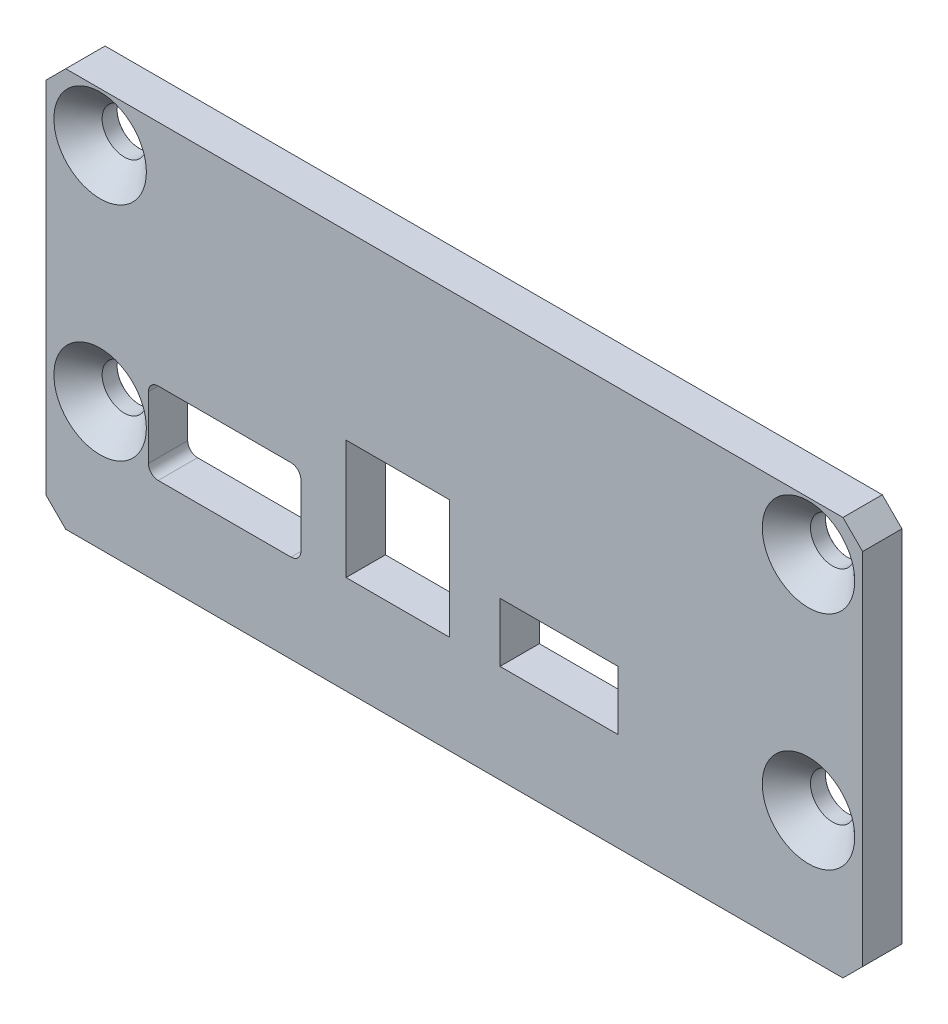
SolidWorks part; units mm, degrees
ref_plane "Plan de face" through (0, 0, 0) normal (0, 0, 1) x (1, 0, 0)
ref_plane "Plan de dessus" through (0, 0, 0) normal (0, 1, 0) x (1, 0, 0)
ref_plane "Plan de droite" through (0, 0, 0) normal (1, 0, 0) x (0, 0, -1)
sketch "Esquisse1" plane through (0, 0, 0) normal (0, 0, 1) x (1, 0, 0)
  line L0 (-24.6565, 17.313) -> (-9.1565, 17.313)
  line L1 (-24.6565, 17.313) -> (-24.6565, 9)
  line L2 (-9.1565, 17.313) -> (-9.1565, 9)
  line L3 (-24.6565, 9) -> (-9.1565, 9)
  line L5 (-32.0565, 33.0905) -> (-32.0565, 15.4495) construction
  line L6 (-28.5565, 2) -> (41.4435, 2) construction
  line L7 (-4.5565, 10) -> (-4.5565, 22.1)
  line L8 (-35.0565, 38.54) -> (-35.0565, 2)
  line L9 (-35.0565, 2) -> (-33.0565, 0)
  line L10 (-33.0565, 0) -> (45.9435, 0)
  line L11 (45.9435, 0) -> (47.9435, 2)
  line L12 (47.9435, 2) -> (47.9435, 38.54)
  line L13 (47.9435, 38.54) -> (45.9435, 40.54)
  line L14 (45.9435, 40.54) -> (-33.0565, 40.54)
  line L15 (-33.0565, 40.54) -> (-35.0565, 38.54)
  line L16 (-35.0565, 38.54) -> (-35.0565, 2)
  line L17 (-35.0565, 2) -> (-33.0565, 0)
  line L18 (-33.0565, 0) -> (45.9435, 0)
  line L19 (45.9435, 0) -> (47.9435, 2)
  line L20 (47.9435, 2) -> (47.9435, 38.54)
  line L21 (47.9435, 38.54) -> (45.9435, 40.54)
  line L22 (45.9435, 40.54) -> (-33.0565, 40.54)
  line L23 (-33.0565, 40.54) -> (-35.0565, 38.54)
  line L24 (-4.5565, 10) -> (5.9435, 10)
  line L25 (-4.5565, 22.1) -> (5.9435, 22.1)
  line L26 (5.9435, 10) -> (5.9435, 22.1)
  line L27 (44.9435, 33.0905) -> (44.9435, 15.4495) construction
  line L28 (11.0863, 16) -> (23.0863, 16)
  line L29 (11.0863, 16) -> (11.0863, 10)
  line L30 (23.0863, 16) -> (23.0863, 10)
  line L31 (11.0863, 10) -> (23.0863, 10)
  dimension "D2" = 7.4
  dimension "D3" = 7
  dimension "D4" = 39
  dimension "D5" = 10.5
  dimension "D6" = 15.5
  dimension "D7" = 8
  dimension "D8" = 12.1
  dimension "D9" = 12
  dimension "D10" = 6
  dimension "D1" = 0
extrude "Boss.-Extru.1" add sketch "Esquisse1" along normal blind 4
sketch "Esquisse3" plane through (0, 0, 4) normal (0, 0, 1) x (1, 0, 0)
  circle A0 centre (-29.5565, 35.54) radius 1.65 construction
  circle A1 centre (-29.5565, 13) radius 1.65 construction
  circle A2 centre (42.4435, 13) radius 1.65 construction
  circle A3 centre (42.4435, 35.54) radius 1.65 construction
  point P0 (-29.5565, 35.54)
  point P1 (42.4435, 13)
  point P2 (-29.5565, 13)
  point P12 (42.4435, 35.54)
hole_wizard "Fraisage pour vis à tête fraisée M41" positions "Esquisse3D1" profile "Esquisse4" countersink size "M4" standard "Ansi Metric" end condition through all
sketch3d "Esquisse3D1"
  point P0 (-29.5565, 35.54, 4)
  point P3 (-29.5565, 13, 4)
  point P6 (42.4435, 13, 4)
  point P9 (42.4435, 35.54, 4)
sketch "Esquisse4" plane through (-29.5565, 35.54, 4) normal (1, 0, 0) x (0, -1, 0)
  line L0 (0, 0) -> (0, 4)
  line L1 (0, 4) -> (2.275, 4)
  line L2 (2.25, 3.975) -> (2.25, 2.45)
  line L3 (2.25, 2.45) -> (4.7, 0)
  line L5 (4.7, 0) -> (0, 0)
  line L6 (-2.25, 2.45) -> (-4.7, 0) construction
  line L7 (2.275, 4) -> (2.25, 3.975)
  line L8 (-2.275, 4) -> (-2.25, 3.975) construction
  line L11 (0, -6.35) -> (0, 107.95) construction
  dimension "Diamètre du perçage jusqu'au prochain" = 4.5
  dimension "Profondeur du perçage jusqu'au prochain" = 4
  dimension "Diamètre du fraisage entrant" = 9.4
  dimension "Angle du fraisage entrant" = 90
  dimension "Diamètre du fraisage débouchant" = 4.55
  dimension "Angle du fraisage débouchant" = 90
fillet "Congé1" radius 1 4 edges at (-24.6565, 17.313, 2) (-9.1565, 17.313, 2) (-9.1565, 9, 2) (-24.6565, 9, 2)
